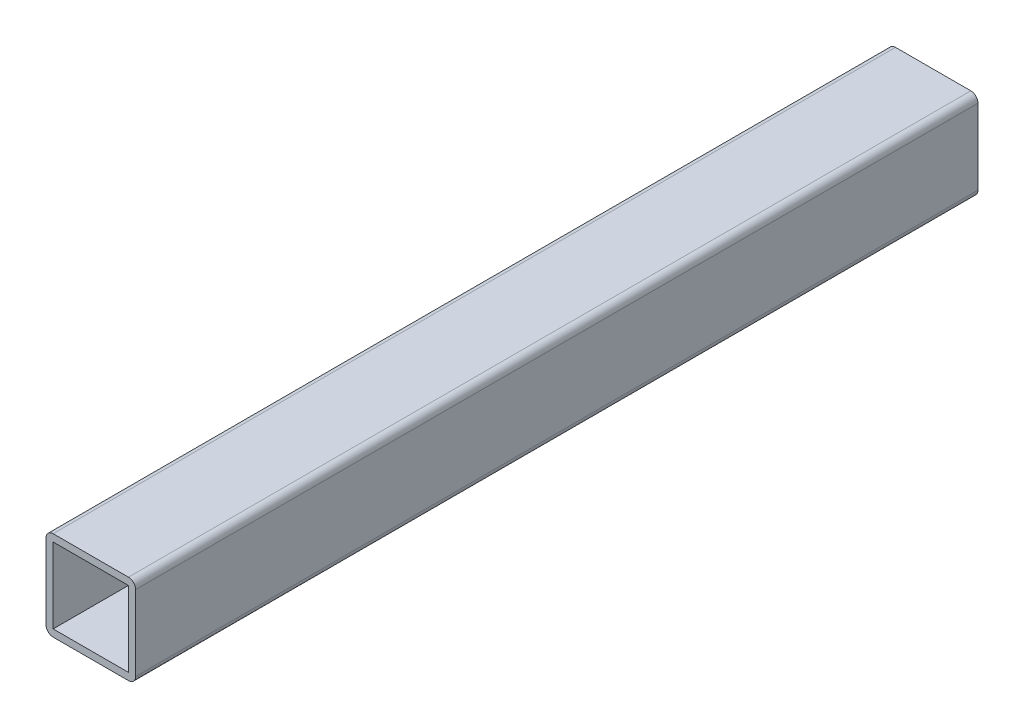
SolidWorks part; units mm, degrees
ref_plane "Спереди" through (0, 0, 0) normal (0, 0, 1) x (1, 0, 0)
ref_plane "Сверху" through (0, 0, 0) normal (0, 1, 0) x (1, 0, 0)
ref_plane "Справа" through (0, 0, 0) normal (1, 0, 0) x (0, 0, -1)
sketch "Эскиз1" plane through (0, 0, 0) normal (0, 0, 1) x (1, 0, 0)
  line L1 (4, 0) -> (46, 0)
  line L2 (0, 4) -> (0, 46)
  line L3 (4, 50) -> (46, 50)
  line L4 (50, 4) -> (50, 46)
  line L5 (4, 46) -> (46, 46)
  line L6 (4, 46) -> (4, 4)
  line L7 (4, 4) -> (46, 4)
  line L8 (46, 46) -> (46, 4)
  arc A0 (0, 46) -> (4, 50) centre (4, 46) cw
  arc A1 (4, 0) -> (0, 4) centre (4, 4) cw
  arc A2 (46, 0) -> (50, 4) centre (46, 4) ccw
  arc A3 (50, 46) -> (46, 50) centre (46, 46) ccw
  point P13 (0, 0)
  point P16 (50, 0)
  point P19 (50, 50)
  dimension "D7" = 4
  dimension "D1" = 50
  dimension "D2" = 50
  dimension "D3" = 4
  dimension "D4" = 4
  dimension "D5" = 4
  dimension "D6" = 4
extrude "Бобышка-Вытянуть1" add sketch "Эскиз1" along normal blind 470
